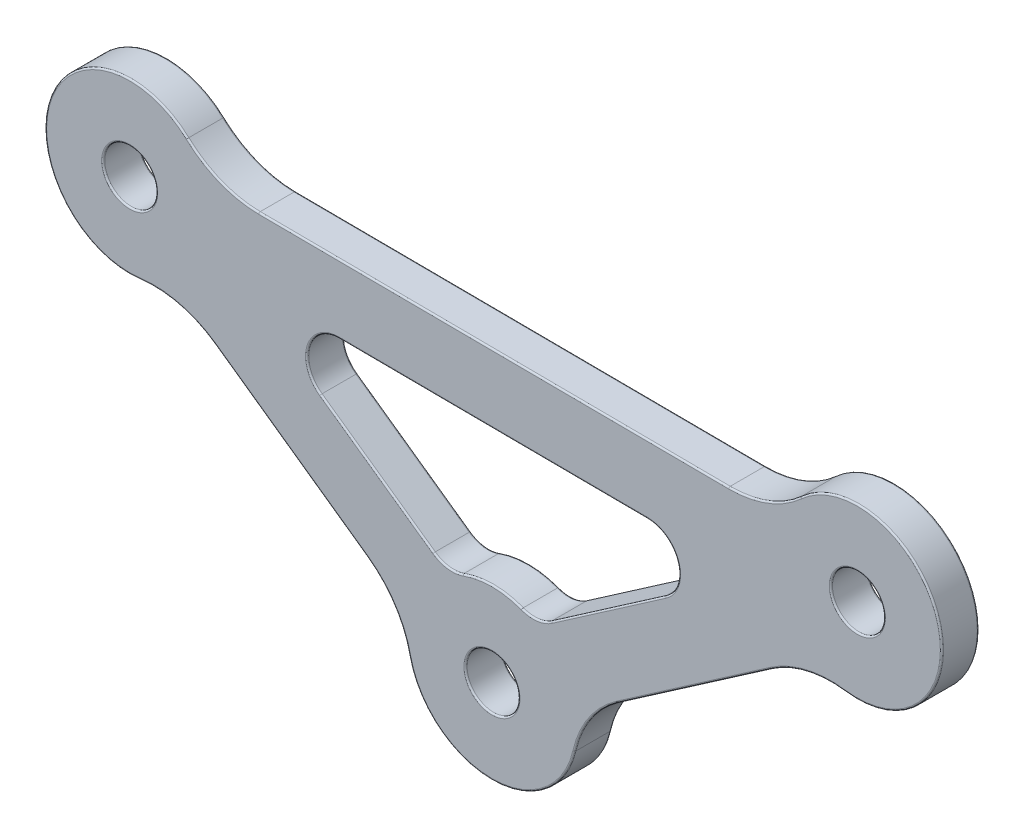
SolidWorks part; units mm, degrees
material "AISI 1020"
ref_plane "Front Plane" through (0, 0, 0) normal (0, 0, 1) x (1, 0, 0)
ref_plane "Top Plane" through (0, 0, 0) normal (0, 1, 0) x (1, 0, 0)
ref_plane "Right Plane" through (0, 0, 0) normal (1, 0, 0) x (0, 0, -1)
sketch "Sketch1" plane through (0, 0, 0) normal (0, 0, 1) x (1, 0, 0)
  line L0 (-56.8732, 200.9695) -> (-91.128, 225.2719) construction
  line L1 (-56.8732, 200.9695) -> (-91.128, 225.2719) construction
  line L2 (-91.128, 225.2719) -> (-22.3206, 224.8466) construction
  line L3 (-91.128, 225.2719) -> (-22.3206, 224.8466) construction
  line L4 (-22.3206, 224.8466) -> (-56.8732, 200.9695) construction
  line L5 (-22.3206, 224.8466) -> (-56.8732, 200.9695) construction
  circle A0 centre (-91.128, 225.2719) radius 8
  circle A1 centre (-22.3206, 224.8466) radius 8
  circle A2 centre (-56.8732, 200.9695) radius 2.5
  circle A3 centre (-22.3206, 224.8466) radius 2.5
  circle A4 centre (-91.128, 225.2719) radius 2.5
  circle A5 centre (-56.8732, 200.9695) radius 8
  dimension "D1" = 16
  dimension "D2" = 5
  dimension "D3" = 5
extrude "Boss-Extrude1" add sketch "Sketch1" along normal blind 3.5
sketch "Sketch2" plane through (0, 0, 3.5) normal (0, 0, 1) x (1, 0, 0)
  line L0 (-29.2243, 224.8893) -> (-84.2243, 225.2292)
  line L1 (-91.128, 225.2719) -> (-22.3206, 224.8466) construction
  line L2 (-86.2345, 221.8001) -> (-61.7667, 204.4412)
  line L3 (-56.8732, 200.9695) -> (-91.128, 225.2719) construction
  line L4 (-51.9371, 204.3805) -> (-27.2567, 221.4356)
  line L5 (-22.3206, 224.8466) -> (-56.8732, 200.9695) construction
  point P12 (-74.0006, 213.1207)
  point P13 (-74.0006, 213.1207)
  point P14 (-39.5969, 212.908)
  point P15 (-39.5969, 212.908)
  point P16 (-56.7243, 225.0592)
  point P17 (-56.7243, 225.0592)
  dimension "D1" = 55
  dimension "D2" = 30
extrude "Extrude-Thin1" add sketch "Sketch2" against normal blind 3.5 thin thin type mid plane wall 6.5
fillet "Fillet1" radius 3 4 edges at (-80.8406, 221.9582, 1.75) (-32.6482, 221.6604, 1.75) (-52.707, 207.799, 1.75) (-60.9547, 207.85, 1.75)
fillet "Fillet2" radius 10 6 edges at (-26.4868, 218.0171, 1.75) (-49.0117, 202.4516, 1.75) (-64.7158, 202.5486, 1.75) (-87.0465, 218.3914, 1.75) (-83.798, 228.4766, 1.75) (-29.6104, 228.1417, 1.75)
fillet "Fillet3" radius 0.15 46 edges at (-54.3732, 200.9695, 0) (-19.8206, 224.8466, 0) (-88.628, 225.2719, 0) (-27.1194, 216.7496, 0) (-14.6761, 227.205, 0) (-30.8472, 228.8324, 0) (-56.7042, 228.3092, 0) (-56.7042, 228.3092, 3.5) (-82.5528, 229.152, 0) (-98.7428, 227.7246, 0) (-86.4296, 217.1162, 0) (-75.8812, 210.47, 0) (-75.8812, 210.47, 3.5) (-66.1232, 202.7096, 0) (-56.9226, 192.9696, 0) (-47.6024, 202.5951, 0) (-37.7493, 210.2343, 0) (-37.7493, 210.2343, 3.5) (-61.0396, 208.3314, 0) (-67.7279, 212.6553, 0) (-67.7279, 212.6553, 3.5) (-74.2001, 219.8193, 0) (-56.7444, 221.8093, 3.5) (-56.7444, 221.8093, 0) (-39.3146, 219.6036, 0) (-45.8749, 212.5202, 3.5) (-45.8749, 212.5202, 0) (-52.6161, 208.2794, 0) (-56.8238, 208.9693, 0) (-54.3732, 200.9695, 3.5) (-19.8206, 224.8466, 3.5) (-88.628, 225.2719, 3.5) (-86.4296, 217.1162, 3.5) (-98.7428, 227.7246, 3.5) (-82.5528, 229.152, 3.5) (-30.8472, 228.8324, 3.5) (-14.6761, 227.205, 3.5) (-27.1194, 216.7496, 3.5) (-47.6024, 202.5951, 3.5) (-56.9226, 192.9696, 3.5) (-66.1232, 202.7096, 3.5) (-74.2001, 219.8193, 3.5) (-61.0396, 208.3314, 3.5) (-56.8238, 208.9693, 3.5) (-52.6161, 208.2794, 3.5) (-39.3146, 219.6036, 3.5)
